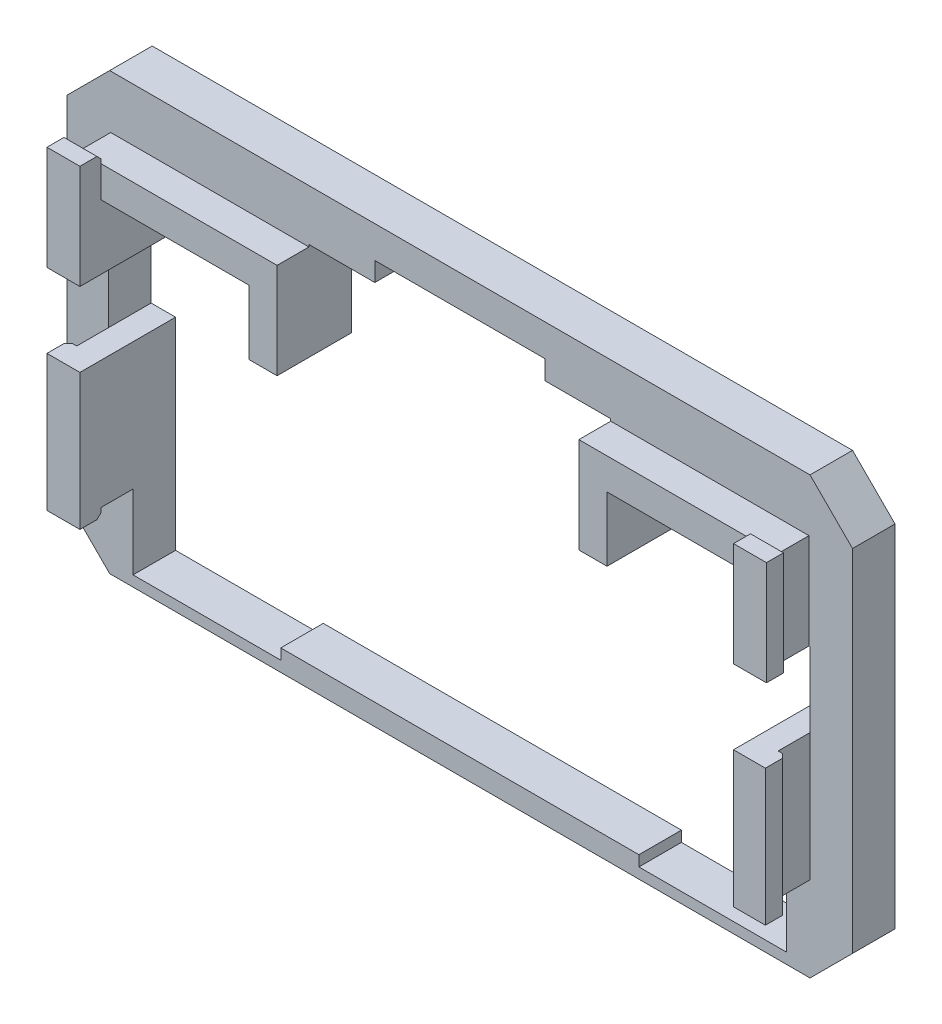
SolidWorks part; units mm, degrees
ref_plane "Front Plane" through (0, 0, 0) normal (0, 0, 1) x (1, 0, 0)
ref_plane "Top Plane" through (0, 0, 0) normal (0, 1, 0) x (1, 0, 0)
ref_plane "Right Plane" through (0, 0, 0) normal (1, 0, 0) x (0, 0, -1)
sketch "Sketch2" plane through (0, 0, 0) normal (0, 0, 1) x (1, 0, 0)
  line L0 (281.4314, 89.4547) -> (281.4314, 94.4547) construction
  line L1 (288.4314, 89.4547) -> (274.4314, 89.4547) construction
  line L2 (285.4314, 90.4547) -> (277.4314, 90.4547)
  line L3 (277.4314, 90.4547) -> (277.4314, 89.5547)
  line L4 (277.4314, 89.5547) -> (274.3314, 89.5547)
  line L5 (274.3314, 89.5547) -> (274.3314, 84.9556)
  line L6 (274.3314, 84.9556) -> (273.0063, 84.9556)
  line L7 (273.0063, 84.9556) -> (273.0063, 87.9858)
  line L8 (273.0063, 87.9858) -> (266.0559, 87.9858)
  line L9 (266.0559, 87.9858) -> (266.0559, 84.9556)
  line L10 (266.0559, 84.9556) -> (262.9558, 84.9556)
  line L11 (262.9558, 84.9556) -> (262.9558, 91.9547)
  line L12 (262.9558, 91.9547) -> (299.907, 91.9547)
  line L13 (274.4314, 89.4547) -> (274.4314, 84.7556) construction
  line L14 (274.4314, 84.7556) -> (272.9063, 84.7556) construction
  line L15 (272.9063, 84.7556) -> (272.9063, 87.9858) construction
  line L17 (266.1559, 84.7556) -> (265.3309, 84.7556) construction
  line L18 (266.1559, 87.9858) -> (266.1559, 84.7556) construction
  line L19 (272.9063, 87.9858) -> (266.1559, 87.9858) construction
  line L20 (299.907, 84.9556) -> (299.907, 91.9547)
  line L21 (296.8069, 84.9556) -> (299.907, 84.9556)
  line L22 (296.8069, 87.9858) -> (296.8069, 84.9556)
  line L23 (289.8565, 87.9858) -> (296.8069, 87.9858)
  line L24 (289.8565, 84.9556) -> (289.8565, 87.9858)
  line L25 (288.5314, 84.9556) -> (289.8565, 84.9556)
  line L26 (288.5314, 89.5547) -> (288.5314, 84.9556)
  line L27 (285.4314, 89.5547) -> (288.5314, 89.5547)
  line L28 (285.4314, 90.4547) -> (285.4314, 89.5547)
  line L30 (262.9558, 81.4554) -> (266.0559, 81.4554)
  line L31 (262.9558, 81.4554) -> (262.9558, 71.4547)
  line L32 (262.9558, 71.4547) -> (266.0559, 71.4547)
  line L33 (266.0559, 81.4554) -> (266.0559, 71.4547)
  line L34 (264.9058, 89.4547) -> (264.9058, 75.4547) construction
  line L35 (266.0559, 71.9547) -> (296.8069, 71.9547)
  line L36 (266.0559, 71.9547) -> (266.0559, 71.4547)
  line L37 (266.0559, 71.4547) -> (296.8069, 71.4547)
  line L38 (296.8069, 71.9547) -> (296.8069, 71.4547)
  line L39 (299.907, 71.4547) -> (296.8069, 71.4547)
  line L40 (299.907, 71.4547) -> (299.907, 81.4554)
  line L41 (299.907, 81.4554) -> (296.8069, 81.4554)
  line L42 (296.8069, 71.4547) -> (296.8069, 81.4554)
  line L43 (262.9558, 84.9556) -> (264.9058, 84.9556)
  line L44 (262.9558, 84.9556) -> (262.9558, 81.4554)
  line L45 (262.9558, 81.4554) -> (264.9058, 81.4554)
  line L46 (264.9058, 84.9556) -> (264.9058, 81.4554)
  line L48 (299.907, 84.9556) -> (297.907, 84.9556)
  line L49 (299.907, 84.9556) -> (299.907, 81.4554)
  line L50 (299.907, 81.4554) -> (297.907, 81.4554)
  line L51 (297.907, 84.9556) -> (297.907, 81.4554)
  point P26 (265.7434, 84.7556)
  point P34 (281.4314, 91.9547)
  point P43 (281.4314, 90.4547)
  point P47 (0, 0)
  point P48 (266.0559, 69.9547)
  point P62 (0, 0)
  point P64 (0, 0)
  point P65 (0, 0)
  point P66 (0, 0)
  dimension "D1" = 0.1
  dimension "D2" = 0.2
  dimension "D3" = 0.1
  dimension "D4" = 0.5
  dimension "D5" = 0.2
  dimension "D6" = 0.1
  dimension "D7" = 0
  dimension "D8" = 0.1
  dimension "D9" = 1
  dimension "D10" = 3
  dimension "D11" = 1.5
extrude "Boss-Extrude1" add sketch "Sketch2" against normal blind 2 contours L2 L0 L12 L11 L10 L9 L8 L7 L6 L5 L4 L3 | L0 L2 L28 L27 L26 L25 L24 L23 L22 L21 L20 L12 | L38 L35 L33 L37 | L33 L30 L31 L32 | L42 L38 L39 L40 L41 | L49 L48 L51 L50 | L44 L43 L46 L45
sketch "Sketch3" plane through (0, 0, 0) normal (0, 0, 1) x (1, 0, 0)
  line L1 (264.9058, 75.4547) -> (267.88, 75.4547) construction
  line L3 (264.9058, 89.4547) -> (297.957, 89.4547) construction
  line L4 (266.0559, 84.9556) -> (265.0058, 84.9556)
  line L5 (266.0559, 81.4554) -> (264.9058, 81.4554)
  line L6 (266.0559, 81.4554) -> (266.0559, 75.4547)
  line L7 (266.0559, 75.4547) -> (264.9058, 75.4547)
  line L8 (264.9058, 81.4554) -> (264.9058, 75.4547)
  line L9 (273.0063, 84.9556) -> (273.0063, 87.9858) construction
  line L10 (266.0559, 84.9556) -> (264.9058, 84.9556) construction
  line L11 (296.8069, 81.4554) -> (297.907, 81.4554)
  line L12 (296.8069, 81.4554) -> (296.8069, 75.4547)
  line L13 (296.8069, 75.4547) -> (297.907, 75.4547)
  line L14 (297.907, 81.4554) -> (297.907, 75.4547)
  line L15 (265.0058, 84.9556) -> (266.0559, 84.9556)
  line L16 (266.0559, 84.9556) -> (266.0559, 87.9858)
  line L17 (266.0559, 87.9858) -> (273.0063, 87.9858)
  line L20 (273.0063, 87.9858) -> (266.0559, 87.9858) construction
  line L21 (272.9063, 87.9858) -> (266.1559, 87.9858) construction
  line L22 (273.0063, 87.9858) -> (273.0063, 84.9556)
  line L24 (273.0063, 84.9556) -> (274.3314, 84.9556)
  line L25 (274.3314, 84.9556) -> (274.3314, 89.4547)
  line L26 (274.3314, 89.4547) -> (265.0058, 89.4547)
  line L27 (265.0058, 89.4547) -> (265.0058, 84.9556)
  line L28 (264.9058, 89.4547) -> (264.9058, 75.4547) construction
  line L30 (288.5314, 84.9556) -> (289.8565, 84.9556)
  line L34 (289.8565, 84.9556) -> (289.8565, 87.9858)
  line L35 (289.8565, 87.9858) -> (296.8069, 87.9858)
  line L36 (296.8069, 87.9858) -> (296.8069, 84.9556)
  line L37 (296.8069, 84.9556) -> (297.857, 84.9556)
  line L38 (296.8069, 84.9556) -> (297.907, 84.9556) construction
  line L39 (297.857, 84.9556) -> (297.857, 89.4547)
  line L60 (274.3314, 89.5547) -> (274.3314, 84.9556) construction
  line L61 (288.4314, 89.4547) -> (274.4314, 89.4547) construction
  line L74 (297.857, 89.4547) -> (288.5314, 89.4547)
  line L75 (288.5314, 89.5547) -> (288.5314, 84.9556) construction
  line L76 (288.5314, 89.4547) -> (288.5314, 84.9556)
  line L79 (297.957, 89.4547) -> (297.957, 75.4547) construction
  dimension "D2" = 0.1
  dimension "D3" = 0.1
extrude "Boss-Extrude2" add sketch "Sketch3" along normal blind 1.5
sketch "Sketch4" plane through (0, 0, 1.5) normal (0, 0, 1) x (1, 0, 0)
  line L0 (281.4314, 89.4547) -> (281.4314, 96.1398) construction
  line L1 (288.4314, 89.4547) -> (274.4314, 89.4547) construction
  line L2 (264.9058, 75.4547) -> (267.88, 75.4547) construction
  line L3 (264.5058, 89.8547) -> (266.0559, 89.8547)
  line L4 (264.5058, 89.8547) -> (264.5058, 84.9556)
  line L5 (264.5058, 84.9556) -> (266.0559, 84.9556)
  line L6 (266.0559, 89.8547) -> (266.0559, 84.9556)
  line L7 (266.0559, 81.4554) -> (264.5058, 81.4554)
  line L8 (298.357, 84.9556) -> (296.8069, 84.9556)
  line L9 (296.8069, 89.8547) -> (296.8069, 84.9556)
  line L10 (298.357, 89.8547) -> (296.8069, 89.8547)
  line L11 (298.357, 89.8547) -> (298.357, 84.9556)
  line L12 (266.0559, 81.4554) -> (266.0559, 75.0547)
  line L13 (264.9058, 89.4547) -> (264.9058, 75.4547) construction
  line L14 (264.9058, 89.4547) -> (297.957, 89.4547) construction
  line L15 (266.0559, 75.0547) -> (264.5058, 75.0547)
  line L16 (264.5058, 81.4554) -> (264.5058, 75.0547)
  line L18 (296.8069, 81.4554) -> (298.307, 81.4554)
  line L19 (296.8069, 81.4554) -> (296.8069, 75.0547)
  line L20 (296.8069, 75.0547) -> (298.307, 75.0547)
  line L21 (298.307, 81.4554) -> (298.307, 75.0547)
  point P31 (0, 0)
  point P32 (0, 0)
  dimension "D1" = 0.4
  dimension "D2" = 0.4
  dimension "D3" = 0.4
extrude "Boss-Extrude3" add sketch "Sketch4" along normal blind 1 contours L6 L3 L4 L5 | L7 L16 L15 L12 | L21 L18 L19 L20 | L11 L10 L9 L8
chamfer "Chamfer1" distance 0.2 angle 45 8 edges at (265.2809, 89.8547, 1.5) (264.5058, 87.4052, 1.5) (297.557, 75.0547, 1.5) (298.307, 78.2551, 1.5) (298.357, 87.4052, 1.5) (297.582, 89.8547, 1.5) (265.2809, 75.0547, 1.5) (264.5058, 78.2551, 1.5)
sketch "Sketch5" plane through (0, 0, -2) normal (0, 0, -1) x (-1, 0, 0)
  line L1 (-267.88, 87.9858) -> (-271.1802, 87.9858)
  line L2 (-267.88, 87.9858) -> (-267.88, 88.9858)
  line L3 (-267.88, 88.9858) -> (-271.1802, 88.9858)
  line L4 (-271.1802, 87.9858) -> (-271.1802, 88.9858)
  line L5 (-267.88, 75.6847) -> (-267.88, 74.4846) construction
  line L6 (-271.1802, 74.4846) -> (-271.1802, 75.6847) construction
  line L7 (-273.0063, 87.9858) -> (-266.0559, 87.9858) construction
  line L8 (-281.4314, 89.4547) -> (-281.4314, 96.8892) construction
  line L9 (-288.4314, 89.4547) -> (-274.4314, 89.4547) construction
  line L10 (-294.9828, 88.9858) -> (-291.6826, 88.9858)
  line L11 (-291.6826, 87.9858) -> (-291.6826, 88.9858)
  line L12 (-294.9828, 87.9858) -> (-291.6826, 87.9858)
  line L13 (-294.9828, 87.9858) -> (-294.9828, 88.9858)
  point P4 (-267.88, 87.9858)
  point P10 (0, 0)
  dimension "D1" = 1
extrude "Cut-Extrude1" cut sketch "Sketch5" against normal up to surface (2 mm away)
sketch "Sketch8" plane through (0, 0, -2) normal (0, 0, -1) x (-1, 0, 0)
  line L0 (-266.0559, 71.9547) -> (-296.8069, 71.9547) construction
  line L1 (-289.8565, 71.9547) -> (-273.0063, 71.9547)
  line L2 (-289.8565, 71.9547) -> (-289.8565, 72.4547)
  line L3 (-289.8565, 72.4547) -> (-273.0063, 72.4547)
  line L4 (-273.0063, 71.9547) -> (-273.0063, 72.4547)
  line L5 (-289.8565, 84.9556) -> (-289.8565, 87.9858) construction
  line L6 (-273.0063, 84.9556) -> (-273.0063, 87.9858) construction
  dimension "D1" = 0.5
extrude "Boss-Extrude4" add sketch "Sketch8" against normal up to surface (2 mm away) up to face at (281.4314, 81.7047, 0)
chamfer "Chamfer2" distance 2 angle 45 4 edges at (262.9558, 91.9547, -1) (262.9558, 71.4547, -1) (299.907, 71.4547, -1) (299.907, 91.9547, -1)
